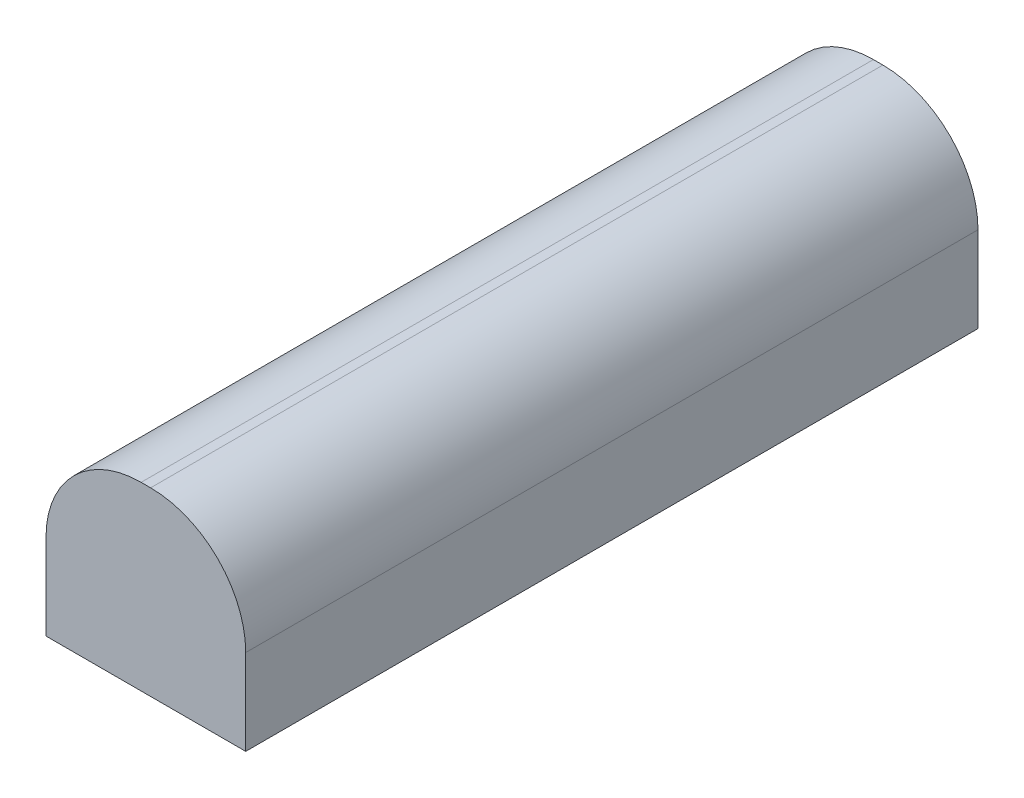
SolidWorks part; units mm, degrees
ref_plane "Front Plane" through (0, 0, 0) normal (0, 0, 1) x (1, 0, 0)
ref_plane "Top Plane" through (0, 0, 0) normal (0, 1, 0) x (1, 0, 0)
ref_plane "Right Plane" through (0, 0, 0) normal (1, 0, 0) x (0, 0, -1)
sketch "Sketch1" plane through (0, 0, 0) normal (0, 1, 0) x (1, 0, 0)
  line L1 (0, 0) -> (21, 0)
  line L2 (0, 0) -> (0, 77)
  line L3 (0, 77) -> (21, 77)
  line L4 (21, 0) -> (21, 77)
  dimension "D1" = 21
  dimension "D2" = 77
extrude "Boss-Extrude1" add sketch "Sketch1" along normal blind 19
fillet "Fillet1" radius 10 2 edges at (0, 19, -38.5) (21, 19, -38.5)
